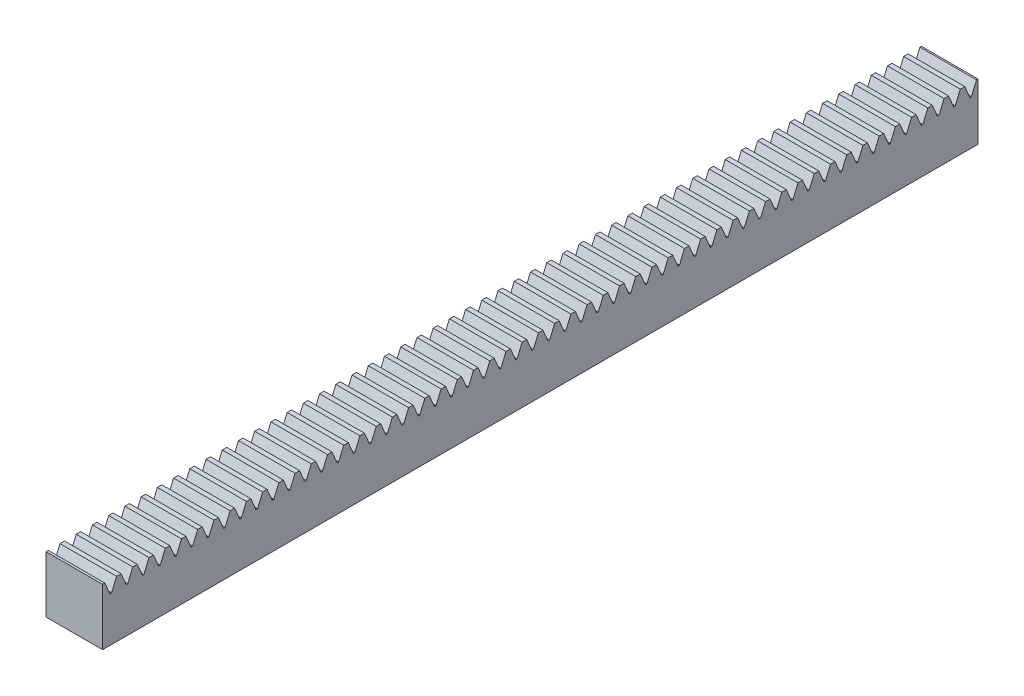
SolidWorks part; units mm, degrees
ref_plane "Front Plane" through (0, 0, 0) normal (0, 0, 1) x (1, 0, 0)
ref_plane "Top Plane" through (0, 0, 0) normal (0, 1, 0) x (1, 0, 0)
ref_plane "Right Plane" through (0, 0, 0) normal (1, 0, 0) x (0, 0, -1)
sketch "Sketch1" plane through (0, 0, 0) normal (0, 0, 1) x (1, 0, 0)
  line L1 (-9.525, 9.525) -> (9.525, 9.525)
  line L2 (-9.525, 9.525) -> (-9.525, -9.525)
  line L3 (-9.525, -9.525) -> (9.525, -9.525)
  line L4 (9.525, 9.525) -> (9.525, -9.525)
  line L5 (-9.525, 9.525) -> (9.525, -9.525) construction
  line L6 (-9.525, -9.525) -> (9.525, 9.525) construction
  point P0 (0, 0)
  dimension "D1" = 19.05
  dimension "D2" = 19.05
extrude "Boss-Extrude1" add sketch "Sketch1" along normal blind 294.64
sketch "Sketch3" plane through (9.525, 0, 0) normal (1, 0, 0) x (0, 0, -1)
  line L0 (-291.9095, 11.9122) -> (-291.9095, -16.3949) construction
  line L1 (-293.878, 9.525) -> (-289.941, 9.525)
  line L2 (-294.64, 9.525) -> (0, 9.525) construction
  line L3 (-289.941, 9.525) -> (-291.6555, 5.461)
  line L4 (-293.878, 9.525) -> (-292.1635, 5.461)
  line L5 (-292.1635, 5.461) -> (-291.6555, 5.461)
  dimension "D1" = 0.762
  dimension "D2" = 0.508
  dimension "D3" = 4.064
  dimension "D4" = 3.937
extrude "Cut-Extrude2" cut sketch "Sketch3" against normal blind 157.48
fillet "Fillet2" radius 0.127 1 edges at (0, 5.461, 292.1635)
fillet "Fillet3" radius 0.127 1 edges at (0, 5.461, 291.6555)
pattern_linear "LPattern6" count 54 spacing 5.461 along (0, 0, -1) of "Cut-Extrude2", "Fillet2", "Fillet3"
